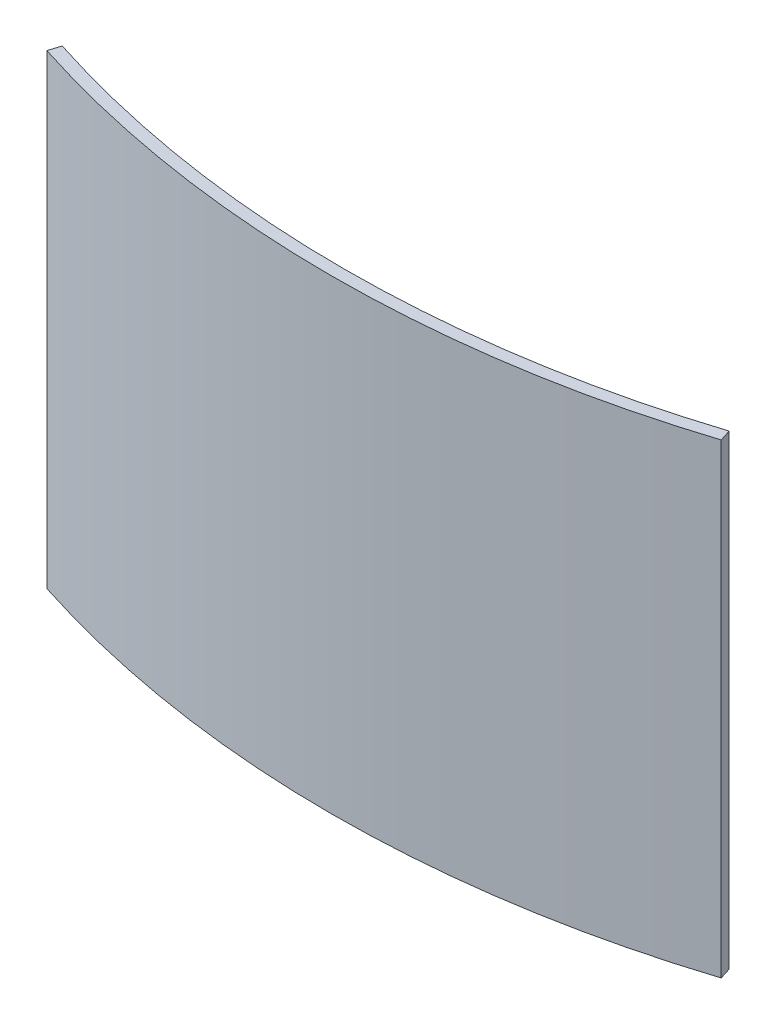
SolidWorks part; units mm, degrees
ref_plane "Plano frontal" through (0, 0, 0) normal (0, 0, 1) x (1, 0, 0)
ref_plane "Plano superior" through (0, 0, 0) normal (0, 1, 0) x (1, 0, 0)
ref_plane "Plano direito" through (0, 0, 0) normal (1, 0, 0) x (0, 0, -1)
sketch "Esboço1" plane through (0, 0, 0) normal (0, 1, 0) x (1, 0, 0)
  line L0 (0, 0) -> (0, -40) construction
  line L1 (0, 0) -> (-275, 0) construction
  line L2 (0, 0) -> (275, 0) construction
  arc A0 (275, 0) -> (-275, 0) centre (0, 856.9568) cw
  dimension "D1" = 275
  dimension "D3" = 40
  dimension "D4" = 900
  dimension "D2" = 275
extrude "Extrusão-Fina1" add sketch "Esboço1" along normal blind 190 and the other way blind 190 thin contours A0
